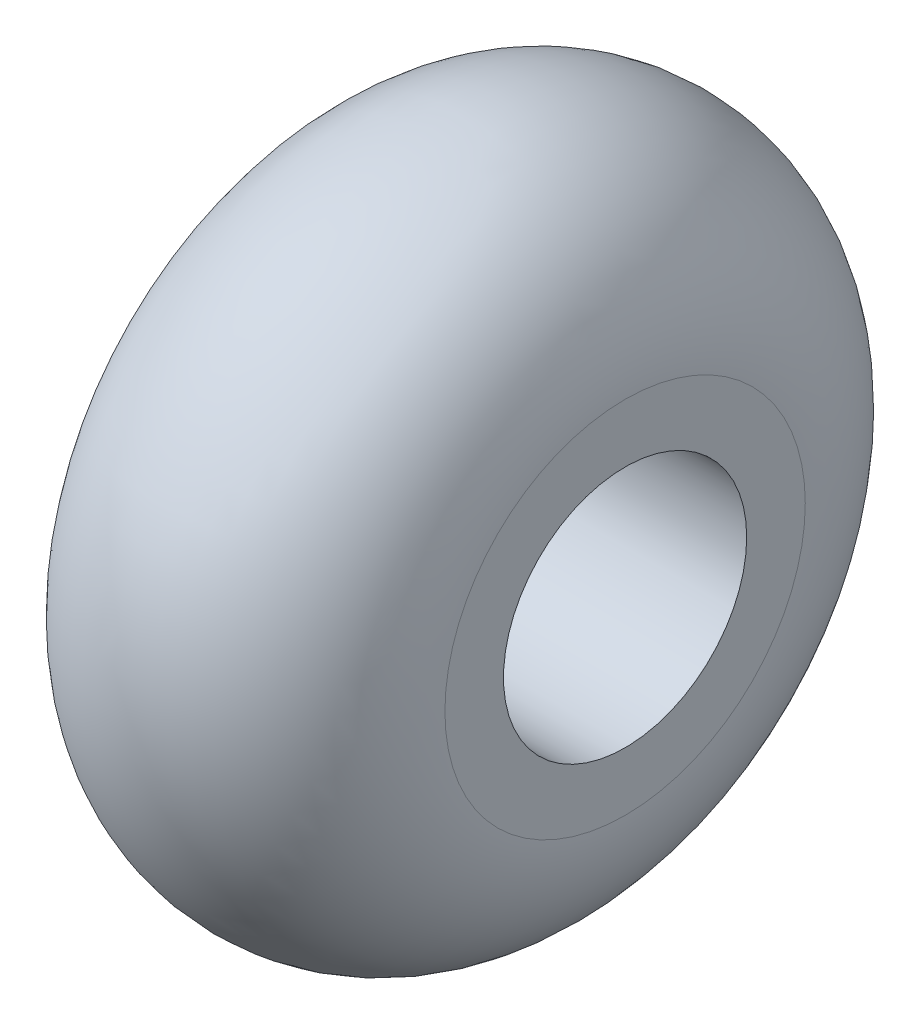
SolidWorks part; units mm, degrees
ref_plane "Front Plane" through (0, 0, 0) normal (0, 0, 1) x (1, 0, 0)
ref_plane "Top Plane" through (0, 0, 0) normal (0, 1, 0) x (1, 0, 0)
ref_plane "Right Plane" through (0, 0, 0) normal (1, 0, 0) x (0, 0, -1)
sketch "Sketch1" plane through (0, 0, 0) normal (0, 0, 1) x (1, 0, 0)
  line L0 (13.6093, 0) -> (0, 0) construction
  line L1 (0, 0) -> (0, 11.2646) construction
  line L2 (11, 4.05) -> (0, 4.05)
  line L3 (0, 4.05) -> (0, 6)
  line L4 (11, 6) -> (11, 4.05)
  arc A0 (0, 6) -> (11, 6) centre (5.5, 6) cw
  dimension "D3" = 5.5
  dimension "D1" = 4.05
  dimension "D2" = 6
  dimension "D4" = 11
revolve "Revolve1" add sketch "Sketch1" angle 360 about L0
